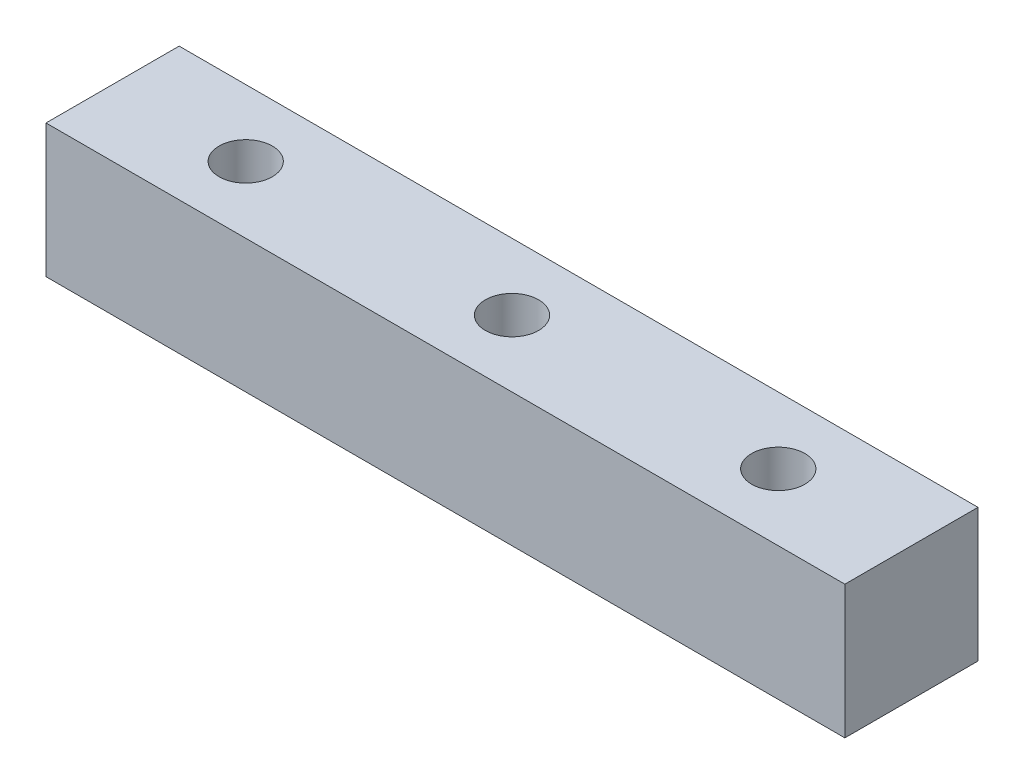
SolidWorks part; units mm, degrees
ref_plane "Front Plane" through (0, 0, 0) normal (0, 0, 1) x (1, 0, 0)
ref_plane "Top Plane" through (0, 0, 0) normal (0, 1, 0) x (1, 0, 0)
ref_plane "Right Plane" through (0, 0, 0) normal (1, 0, 0) x (0, 0, -1)
sketch "Sketch1" plane through (0, 0, 0) normal (0, 1, 0) x (1, 0, 0)
  line L1 (0, 0) -> (60, 0)
  line L2 (0, 0) -> (0, 10)
  line L3 (0, 10) -> (60, 10)
  line L4 (60, 0) -> (60, 10)
  circle A0 centre (10, 5) radius 2
  circle A1 centre (30, 5) radius 2
  circle A2 centre (50, 5) radius 2
  dimension "D3" = 10
  dimension "D9" = 4
  dimension "D10" = 4
  dimension "D11" = 4
  dimension "D1" = 10
  dimension "D2" = 60
  dimension "D4" = 30
  dimension "D5" = 10
  dimension "D6" = 5
  dimension "D7" = 5
  dimension "D8" = 5
extrude "Boss-Extrude1" add sketch "Sketch1" along normal blind 10
